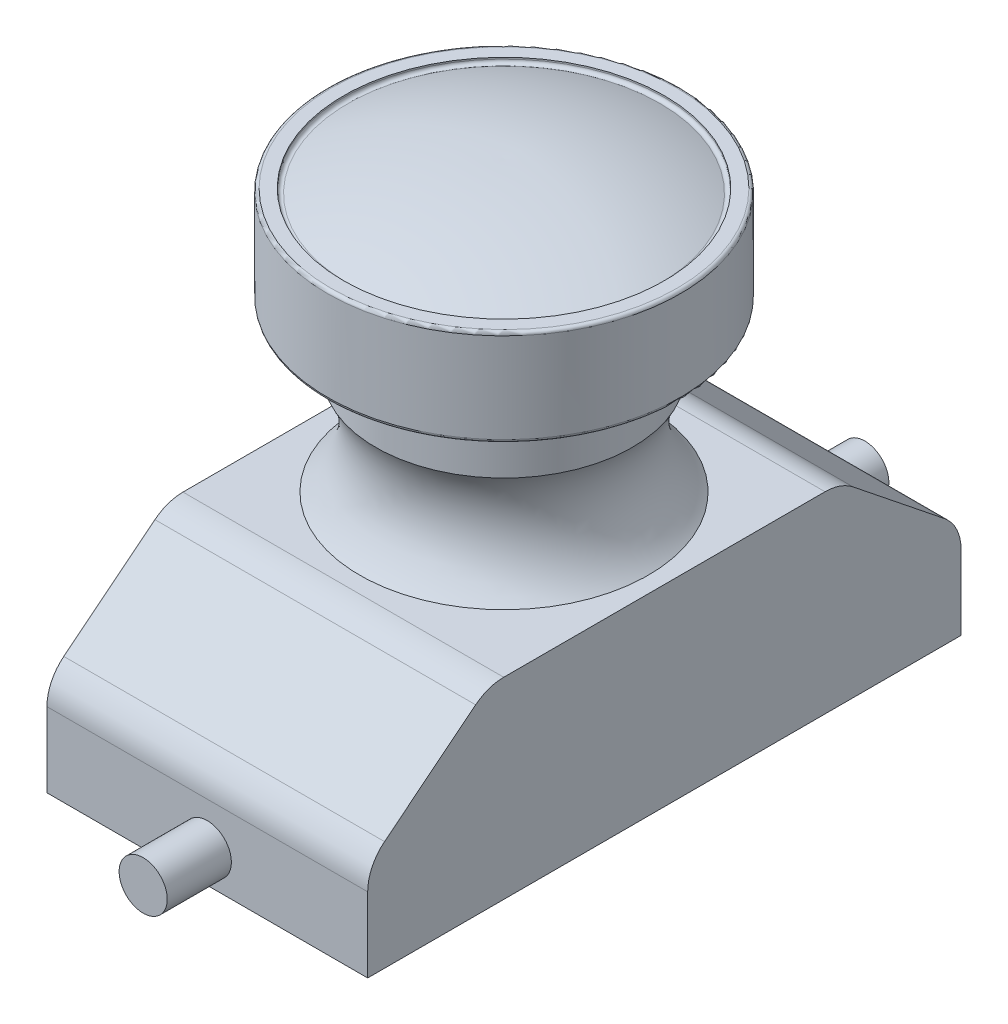
SolidWorks part; units mm, degrees
ref_plane "Ön Düzlem" through (0, 0, 0) normal (0, 0, 1) x (1, 0, 0)
ref_plane "Üst Düzlem" through (0, 0, 0) normal (0, 1, 0) x (1, 0, 0)
ref_plane "Sağ Düzlem" through (0, 0, 0) normal (1, 0, 0) x (0, 0, -1)
sketch "Çizim1" plane through (0, 0, 0) normal (1, 0, 0) x (0, 0, -1)
  line L15 (-9.25, 0) -> (9.25, 0)
  line L16 (9.25, 0) -> (9.25, 3)
  line L20 (-9.25, 3) -> (-9.25, 0)
  line L21 (0, 0) -> (0, 7.3127) construction
  line L22 (-5.5, 6) -> (0, 6)
  line L23 (0, 6) -> (5.5, 6)
  line L24 (-9.25, 3) -> (-5.5, 6)
  line L25 (5.5, 6) -> (9.25, 3)
  dimension "D10" = 18.5
  dimension "D11" = 5.5
  dimension "D12" = 3
  dimension "D13" = 5.5
  dimension "D14" = 3
extrude "Yükseklik-Ekstrüzyon1" add sketch "Çizim1" along normal mid plane 10
sketch "Çizim2" plane through (0, 0, 0) normal (1, 0, 0) x (0, 0, -1)
  line L0 (0, 6) -> (0, 14)
  line L1 (-5.5, 6) -> (5.5, 6) construction
  line L2 (0, 14) -> (5, 14)
  line L3 (5, 14) -> (5, 14.2)
  line L4 (5, 14.2) -> (5.5, 14.2)
  line L5 (5.5, 14.2) -> (5.5, 11.2)
  line L6 (5.5, 11.2) -> (4, 11.2)
  line L7 (4, 11.2) -> (4, 9.2)
  line L8 (0, 6) -> (4.5, 6)
  arc A0 (4.5, 6) -> (4, 9.2) centre (6.1318, 7.894) cw
  dimension "D8" = 2.5
  dimension "D1" = 4.5
  dimension "D2" = 0.2
  dimension "D3" = 5
  dimension "D4" = 0.5
  dimension "D5" = 3
  dimension "D6" = 8
  dimension "D7" = 2
  dimension "D9" = 1.5
revolve "Döndür4" add sketch "Çizim2" angle 360 about L0
sketch "Çizim3" plane through (0, 0, 0) normal (1, 0, 0) x (0, 0, -1)
  line L1 (5, 14.2) -> (-5, 14.2) construction
  line L2 (0, 15) -> (0, 14.2)
  line L3 (0, 14.2) -> (0, 14)
  line L4 (0, 14) -> (-5, 14)
  arc A0 (-5, 14) -> (0, 15) centre (-0.2003, 3.0017) cw
  dimension "D3" = 12
  dimension "D1" = 0.8
  dimension "D2" = 0.2
  dimension "D4" = 5
revolve "Döndür6" add sketch "Çizim3" angle 360 about L2
fillet "Radyus1" radius 0.1 2 edges at (0, 11.2, -5.5) (0, 14.2, -5.5)
fillet "Radyus2" radius 0.1 1 edges at (0, 14, 5)
fillet "Radyus3" radius 1.4 4 edges at (0, 3, -9.25) (0, 6, -5.5) (0, 3, 9.25) (0, 6, 5.5)
sketch "Çizim4" plane through (0, 0, -9.25) normal (0, 0, -1) x (-1, 0, 0)
  circle A0 centre (0, 1) radius 0.75
  dimension "D1" = 1
extrude "Yükseklik-Ekstrüzyon2" add sketch "Çizim4" along normal blind 2 contours A0
mirror "Aynalama1" about plane through (0, 0, 0) normal (0, 0, 1) of "Yükseklik-Ekstrüzyon2"
